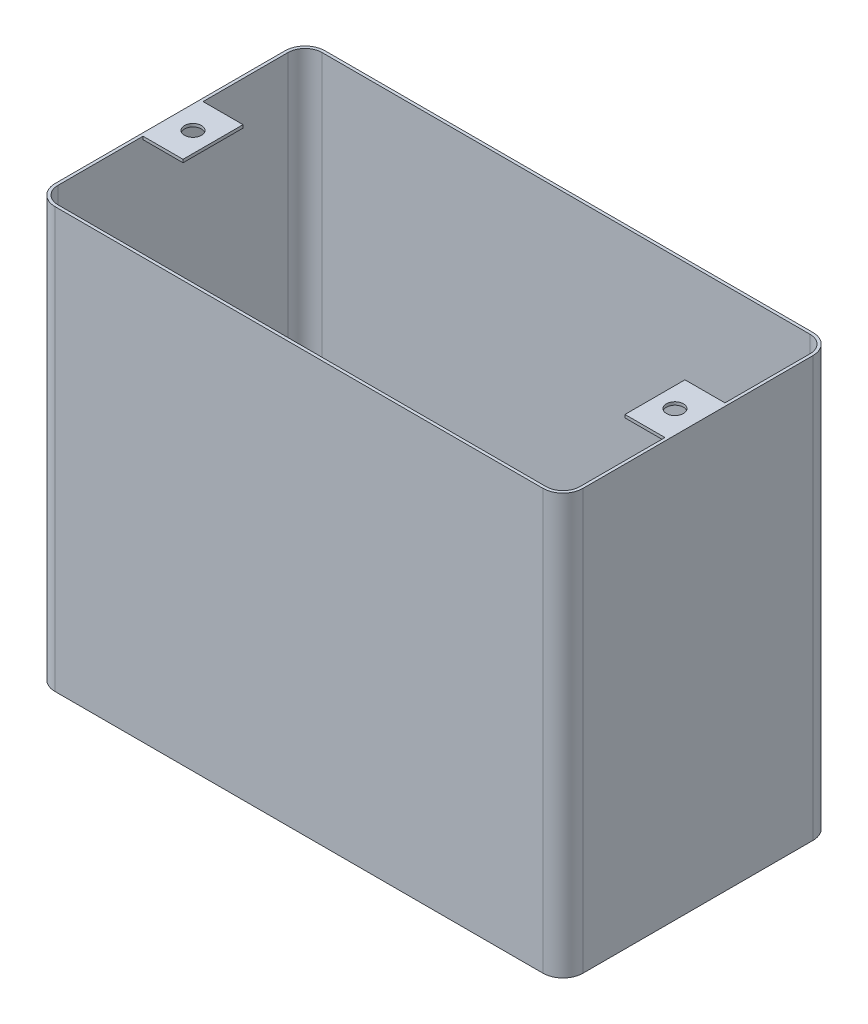
SolidWorks part; units mm, degrees
material "C40 or 38NiCrMo4"
ref_plane "Piano frontale" through (0, 0, 0) normal (0, 0, 1) x (1, 0, 0)
ref_plane "Piano superiore" through (0, 0, 0) normal (0, 1, 0) x (1, 0, 0)
ref_plane "Piano destro" through (0, 0, 0) normal (1, 0, 0) x (0, 0, -1)
sketch "Schizzo1" plane through (0, 0, 0) normal (0, 1, 0) x (1, 0, 0)
  line L1 (10, 0) -> (254, 0)
  line L2 (0, 10) -> (0, 125)
  line L3 (10, 135) -> (254, 135)
  line L4 (264, 10) -> (264, 125)
  arc A0 (254, 135) -> (264, 125) centre (254, 125) cw
  arc A1 (254, 0) -> (264, 10) centre (254, 10) ccw
  arc A2 (10, 0) -> (0, 10) centre (10, 10) cw
  arc A3 (0, 125) -> (10, 135) centre (10, 125) cw
  point P9 (264, 0)
  point P12 (0, 0)
  point P15 (0, 135)
  dimension "D3" = 10
  dimension "D1" = 264
  dimension "D2" = 135
extrude "Estrusione-Sottile1" add sketch "Schizzo1" along normal blind 210 thin thin type one direction reverse wall 1.5
sketch "Schizzo2" plane through (0, 210, 0) normal (0, 1, 0) x (1, 0, 0)
  line L0 (-998.5, 67.5) -> (49001.5, 67.5) construction
  line L1 (1.5, 125) -> (1.5, 10) construction
  line L2 (132, -865) -> (132, 49135) construction
  line L3 (254, 135) -> (10, 135) construction
  line L4 (1.5, 52.5) -> (21.5, 52.5)
  line L5 (242.5, 52.5) -> (242.5, 82.5)
  line L6 (1.5, 52.5) -> (1.5, 82.5)
  line L7 (1.5, 82.5) -> (21.5, 82.5)
  line L8 (21.5, 52.5) -> (21.5, 82.5)
  line L9 (262.5, 82.5) -> (242.5, 82.5)
  line L10 (262.5, 52.5) -> (262.5, 82.5)
  line L11 (262.5, 52.5) -> (242.5, 52.5)
  circle A0 centre (11.5, 67.5) radius 4.25
  circle A1 centre (252.5, 67.5) radius 4.25
  point P5 (1.5, 67.5)
  point P10 (132, 135)
  point P15 (21.5, 67.5)
  point P16 (1.5, 67.5)
  point P24 (262.5, 67.5)
  point P25 (242.5, 67.5)
  dimension "D4" = 8.5
  dimension "D1" = 20
  dimension "D2" = 15
  dimension "D3" = 10
extrude "Estrusione-Estrusione1" add sketch "Schizzo2" against normal blind 1.5
ref_plane "Piano1" through (132, 0, 0) normal (1, 0, 0) x (0, 0, -1)
ref_plane "Piano2" through (0, 0, -67.5) normal (0, 0, 1) x (1, 0, 0)
